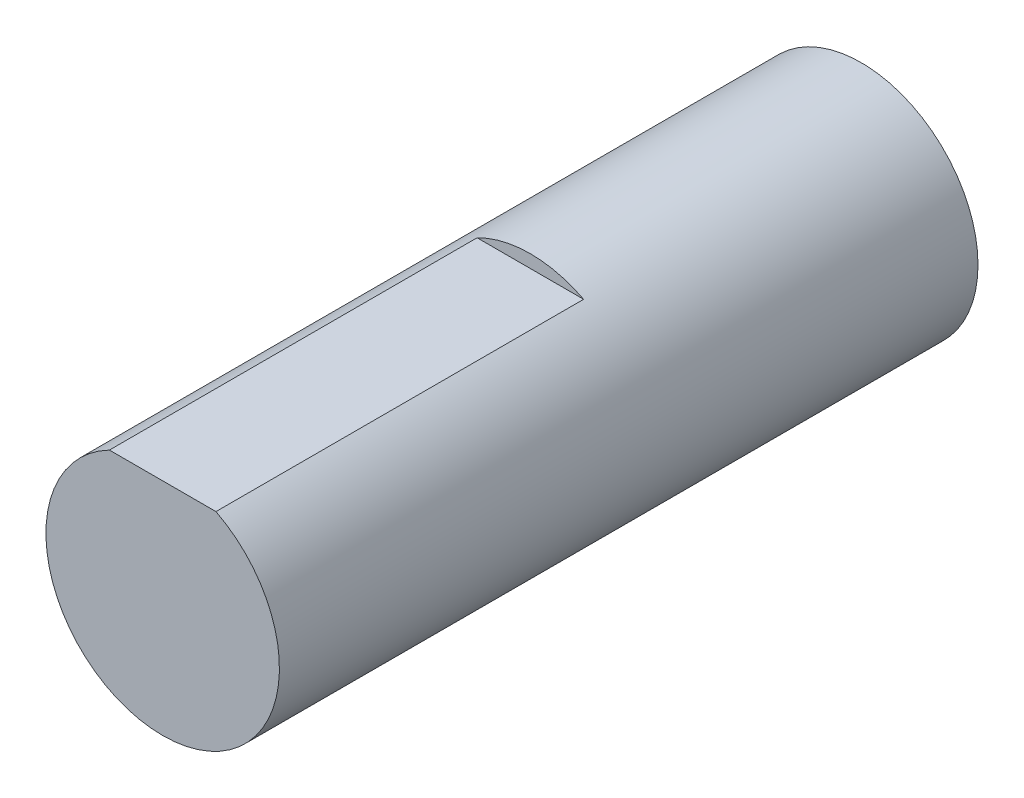
SolidWorks part; units mm, degrees
ref_plane "Front Plane" through (0, 0, 0) normal (0, 0, 1) x (1, 0, 0)
ref_plane "Top Plane" through (0, 0, 0) normal (0, 1, 0) x (1, 0, 0)
ref_plane "Right Plane" through (0, 0, 0) normal (1, 0, 0) x (0, 0, -1)
sketch "Sketch1" plane through (0, 0, 0) normal (0, 0, 1) x (1, 0, 0)
  circle A0 centre (0, 0) radius 3.175
  dimension "D1" = 6.35
extrude "Boss-Extrude1" add sketch "Sketch1" along normal blind 19
sketch "Sketch2" plane through (0, 0, 19) normal (0, 0, 1) x (1, 0, 0)
  line L1 (-1.4491, 2.825) -> (1.4491, 2.825)
  line L2 (-1.4491, 2.825) -> (-1.4491, 3.175)
  line L3 (-1.4491, 3.175) -> (1.4491, 3.175)
  line L4 (1.4491, 2.825) -> (1.4491, 3.175)
  circle A0 centre (0, 0) radius 3.175 construction
  point P8 (0, -3.175)
  dimension "D1" = 6
extrude "Cut-Extrude1" cut sketch "Sketch2" against normal blind 10
